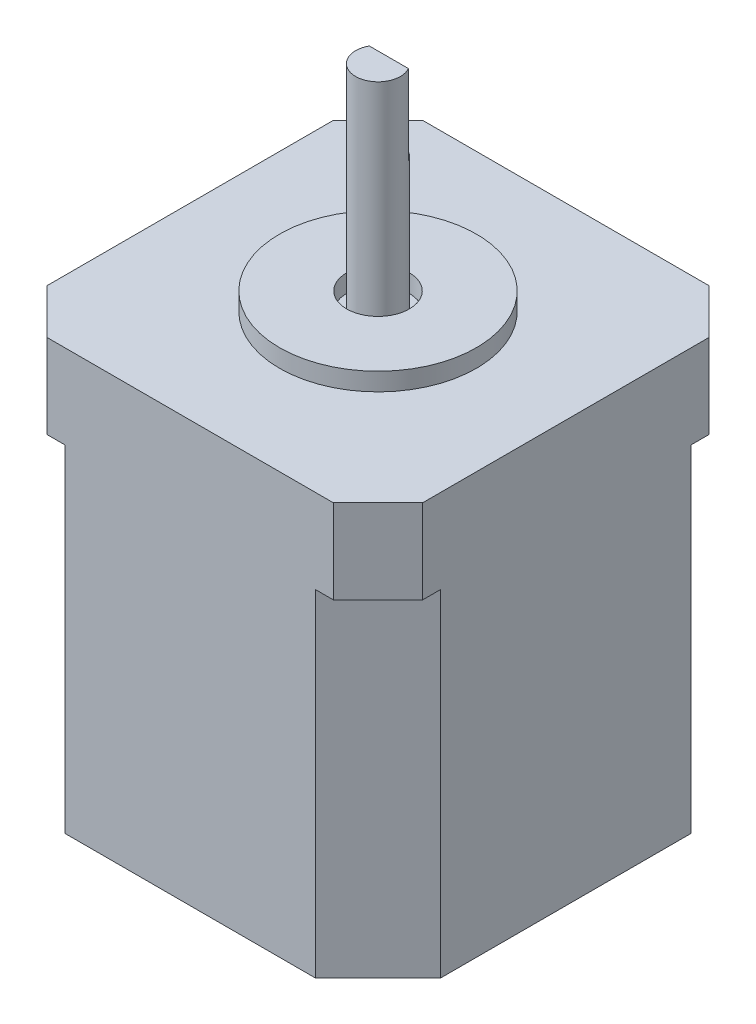
SolidWorks part; units mm, degrees
ref_plane "Front Plane" through (0, 0, 0) normal (0, 0, 1) x (1, 0, 0)
ref_plane "Top Plane" through (0, 0, 0) normal (0, 1, 0) x (1, 0, 0)
ref_plane "Right Plane" through (0, 0, 0) normal (1, 0, 0) x (0, 0, -1)
sketch "Sketch4" plane through (0, 0, 0) normal (0, 1, 0) x (1, 0, 0)
  line L1 (-21, -21) -> (21, -21)
  line L2 (-21, -21) -> (-21, 21)
  line L3 (-21, 21) -> (21, 21)
  line L4 (21, -21) -> (21, 21)
  line L5 (-21, -21) -> (21, 21) construction
  line L6 (-21, 21) -> (21, -21) construction
  point P0 (0, 0)
  dimension "D1" = 42
  dimension "D2" = 42
extrude "Bottom" add sketch "Sketch4" along normal blind 9.4 contours L2 L3 L4 L1
chamfer "Chamfer2" distance 5 angle 45 4 edges at (-21, 4.7, 21) (-21, 4.7, -21) (21, 4.7, 21) (21, 4.7, -21)
sketch "Sketch6" plane through (0, 9.4, 0) normal (0, 1, 0) x (1, 0, 0)
  line L1 (-21, -21) -> (21, -21)
  line L2 (-21, -21) -> (-21, 21)
  line L3 (-21, 21) -> (21, 21)
  line L4 (21, -21) -> (21, 21)
  line L5 (-21, -21) -> (21, 21) construction
  line L6 (-21, 21) -> (21, -21) construction
  point P0 (0, 0)
  dimension "D1" = 42
  dimension "D2" = 42
extrude "Middle" add sketch "Sketch6" along normal blind 28.2
chamfer "Chamfer3" distance 7 angle 45 4 edges at (21, 23.5, 21) (-21, 23.5, 21) (-21, 23.5, -21) (21, 23.5, -21)
sketch "Sketch8" plane through (0, 37.6, 0) normal (0, 1, 0) x (1, 0, 0)
  line L1 (-21, -21) -> (21, -21)
  line L2 (-21, -21) -> (-21, 21)
  line L3 (-21, 21) -> (21, 21)
  line L4 (21, -21) -> (21, 21)
  line L5 (-21, -21) -> (21, 21) construction
  line L6 (-21, 21) -> (21, -21) construction
  point P0 (0, 0)
  dimension "D1" = 42
  dimension "D2" = 42
extrude "Top" add sketch "Sketch8" along normal blind 9.4
chamfer "Chamfer4" distance 5 angle 45 4 edges at (-21, 42.3, 21) (21, 42.3, 21) (-21, 42.3, -21) (21, 42.3, -21)
sketch "Sketch9" plane through (0, 47, 0) normal (0, 1, 0) x (1, 0, 0)
  circle A0 centre (0, 0) radius 11
  circle A1 centre (0, 0) radius 3.5
  point P4 (0, 0)
  dimension "D1" = 22
  dimension "D2" = 7
extrude "Boss-Extrude4" add sketch "Sketch9" along normal blind 2 contours A0 | A1
sketch "Sketch10" plane through (0, 47, 0) normal (0, 1, 0) x (1, 0, 0)
  circle A0 centre (0, 0) radius 2.5
  dimension "D1" = 5
extrude "Shaft" add sketch "Sketch10" along normal blind 24
sketch "Sketch11" plane through (0, 0, 0) normal (1, 0, 0) x (0, 0, -1)
  line L0 (2.5, 47) -> (-2.5, 47) construction
  line L1 (3.4584, 73.2425) -> (1.2188, 73.2425)
  line L2 (3.4584, 73.2425) -> (3.4584, 62)
  line L3 (3.4584, 62) -> (1.2188, 62)
  line L4 (1.2188, 73.2425) -> (1.2188, 62)
  dimension "D1" = 15
extrude "Cut-Extrude3" cut sketch "Sketch11" against normal blind 5 and the other way blind 5
